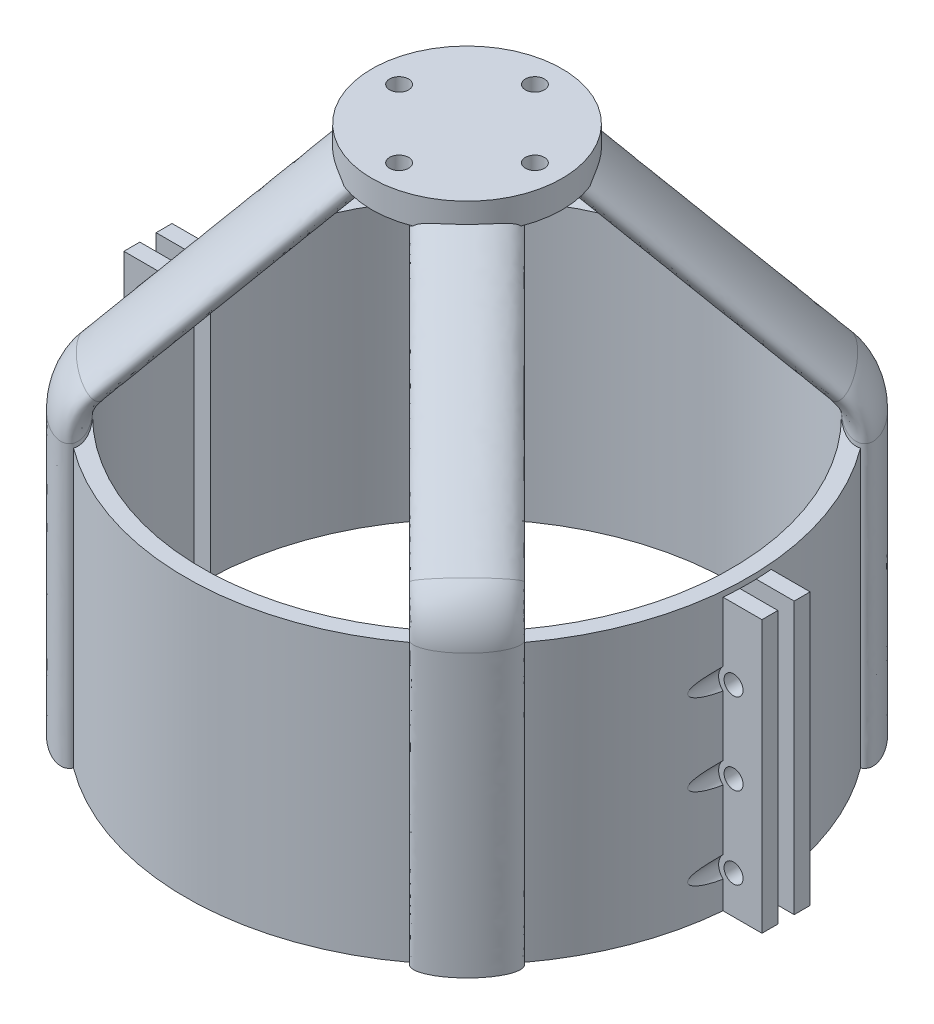
SolidWorks part; units mm, degrees
ref_plane "Front Plane" through (0, 0, 0) normal (0, 0, 1) x (1, 0, 0)
ref_plane "Top Plane" through (0, 0, 0) normal (0, 1, 0) x (1, 0, 0)
ref_plane "Right Plane" through (0, 0, 0) normal (1, 0, 0) x (0, 0, -1)
sketch "Sketch1" plane through (0, 0, 0) normal (0, 1, 0) x (1, 0, 0)
  line L0 (-68.1891, 0) -> (51.75, 0) construction
  line L1 (-58.7269, -1.5) -> (-48.7269, -1.5)
  line L2 (-58.7269, 1.5) -> (-48.7269, 1.5)
  line L3 (-58.7269, -1.5) -> (-58.7269, -4.432)
  line L4 (-58.7269, -4.432) -> (-51.5599, -4.432)
  line L5 (-58.7269, 1.5) -> (-58.7269, 4.432)
  line L6 (-58.7269, 4.432) -> (-51.5599, 4.432)
  line L7 (0, -59.7416) -> (0, 60.0429) construction
  line L8 (58.7269, -1.5) -> (48.7269, -1.5)
  line L9 (58.7269, -4.432) -> (51.5599, -4.432)
  line L10 (58.7269, -1.5) -> (58.7269, -4.432)
  line L11 (58.7269, 1.5) -> (48.7269, 1.5)
  line L12 (58.7269, 1.5) -> (58.7269, 4.432)
  line L13 (58.7269, 4.432) -> (51.5599, 4.432)
  arc A0 (-48.7269, -1.5) -> (48.7269, -1.5) centre (0, 0) ccw
  arc A1 (-51.75, 0) -> (-51.7283, -1.5) centre (0, 0) ccw
  circle A2 centre (0, 0) radius 51.75 construction
  circle A3 centre (0, 0) radius 48.75 construction
  arc A4 (-51.5599, -4.432) -> (51.5599, -4.432) centre (0, 0) ccw
  arc A5 (48.7269, 1.5) -> (-48.7269, 1.5) centre (0, 0) ccw
  arc A6 (51.5599, 4.432) -> (-51.5599, 4.432) centre (0, 0) ccw
  dimension "D1" = 97.5
  dimension "D3" = 3
  dimension "D4" = 10
  dimension "D2" = 3
extrude "Boss-Extrude1" add sketch "Sketch1" along normal blind 50 contours L4 A4 L9 L10 L8 A0 L1 L3 | A6 L6 L5 L2 A5 L11 L12 L13
sketch "Sketch2" plane through (0, 0, 4.432) normal (0, 0, 1) x (1, 0, 0)
  line L0 (0, 57.4382) -> (0, -5.5464) construction
  line L1 (-53.5, 59.7194) -> (-53.5, -8.2171) construction
  line L2 (-58.7269, 0) -> (-51.5599, 0) construction
  circle A0 centre (-53.5, 7) radius 1.75
  circle A1 centre (-53.5, 22) radius 1.75
  circle A2 centre (-53.5, 37) radius 1.75
  circle A3 centre (53.5, 7) radius 1.75
  circle A4 centre (53.5, 22) radius 1.75
  circle A5 centre (53.5, 37) radius 1.75
  dimension "D5" = 3.5
  dimension "D6" = 3.5
  dimension "D7" = 3.5
  dimension "D1" = 53.5
  dimension "D2" = 7
  dimension "D3" = 15
  dimension "D4" = 15
extrude "Cut-Extrude1" cut sketch "Sketch2" against normal through all
sketch "Sketch3" plane through (0, 0, 4.432) normal (0, 0, 1) x (1, 0, 0)
  line L0 (0, 54.5816) -> (0, -6.8451) construction
  circle A0 centre (-53.5, 37) radius 2.75
  circle A1 centre (-53.5, 22) radius 2.75
  circle A2 centre (-53.5, 7) radius 2.75
  circle A3 centre (53.5, 7) radius 2.75
  circle A4 centre (53.5, 22) radius 2.75
  circle A5 centre (53.5, 37) radius 2.75
  circle A6 centre (53.5, 7) radius 1.75 construction
  circle A7 centre (53.5, 22) radius 1.75 construction
  circle A8 centre (53.5, 37) radius 1.75 construction
  circle A9 centre (-53.5, 7) radius 1.75 construction
  circle A10 centre (-53.5, 22) radius 1.75 construction
  circle A11 centre (-53.5, 37) radius 1.75 construction
  circle A12 centre (53.5, 7) radius 1.75
  circle A13 centre (53.5, 22) radius 1.75
  circle A14 centre (53.5, 37) radius 1.75
  circle A15 centre (-53.5, 7) radius 1.75
  circle A16 centre (-53.5, 22) radius 1.75
  circle A17 centre (-53.5, 37) radius 1.75
  dimension "D2" = 5.5
  dimension "D3" = 5.5
  dimension "D4" = 5.5
extrude "Cut-Extrude3" cut sketch "Sketch3" along normal blind 50
ref_plane "Plane1" through (0, 0, 0) normal (0, 0, 1) x (0, -1, 0)
sketch "Sketch5" plane through (0, 0, -4.432) normal (0, 0, -1) x (-1, 0, 0)
  line L0 (0, 54.4273) -> (0, -7.504) construction
  line L1 (0, 50) -> (0, 0) construction
  circle A0 centre (53.5, 7) radius 1.75 construction
  circle A1 centre (53.5, 22) radius 1.75 construction
  circle A2 centre (53.5, 37) radius 1.75 construction
  circle A3 centre (-53.5, 7) radius 1.75 construction
  circle A4 centre (-53.5, 22) radius 1.75 construction
  circle A5 centre (-53.5, 37) radius 1.75 construction
  circle A6 centre (53.5, 7) radius 1.75
  circle A7 centre (53.5, 22) radius 1.75
  circle A8 centre (53.5, 37) radius 1.75
  circle A9 centre (-53.5, 7) radius 1.75
  circle A10 centre (-53.5, 22) radius 1.75
  circle A11 centre (-53.5, 37) radius 1.75
  circle A12 centre (-53.5, 37) radius 2.75
  circle A13 centre (-53.5, 22) radius 2.75
  circle A14 centre (-53.5, 7) radius 2.75
  circle A15 centre (53.5, 7) radius 2.75
  circle A16 centre (53.5, 22) radius 2.75
  circle A17 centre (53.5, 37) radius 2.75
  dimension "D1" = 5.5
  dimension "D2" = 5.5
  dimension "D3" = 5.5
extrude "Cut-Extrude4" cut sketch "Sketch5" along normal blind 50
sketch "Sketch7" plane through (0, 50, 0) normal (0, 1, 0) x (1, 0, 0)
  line L0 (0, 0) -> (-68.3441, -68.3441) construction
ref_plane "Plane2" through (0, 0, 0) normal (0.7071, 0, 0.7071) x (0.7071, 0, -0.7071)
sketch "Sketch9" plane through (0, 0, 0) normal (0.7071, 0, 0.7071) x (0.7071, 0, -0.7071)
  line L2 (0, 50) -> (0, 113.0394) construction
  line L3 (0, 50) -> (-96.6532, 50) construction
  line L4 (48.75, 50) -> (-33.3945, 50) construction
  line L5 (0, 50) -> (0, 0) construction
  line L6 (-24.7578, 95) -> (27.1814, 95) construction
  line L8 (-51.75, 0) -> (-51.75, 51.7721)
  line L16 (-51.75, 0) -> (33.3244, 0) construction
  line L17 (-48.7564, 58.9073) -> (-12, 95)
  arc A0 (-51.75, 51.7721) -> (-48.7564, 58.9073) centre (-41.75, 51.7721) cw
  dimension "D4" = 10
  dimension "D1" = 45
  dimension "D2" = 12
  dimension "D3" = 51.75
sketch "Sketch10" plane through (0, 0, 0) normal (0, -1, 0) x (1, 0, 0)
  line L0 (0, 0) -> (-68.3441, 68.3441) construction
  line L1 (-34.476, 34.476) -> (-8.4853, 8.4853) construction
  ellipse E0 centre (-36.5928, 36.5928) end of major axis (-31.2895, 41.8961) minor radius 3
  point P31 (0, 0)
  dimension "D1" = 6
  dimension "D2" = 15
sweep "Sweep1" add profiles "Sketch10" path "Sketch9"
sketch "Sketch11" plane through (0, 50, 0) normal (0, 1, 0) x (1, 0, 0)
  circle A0 centre (0, 0) radius 48.75
  circle A1 centre (0, 0) radius 51.75
extrude "Boss-Extrude2" add sketch "Sketch11" along normal blind 1
pattern_circular "CirPattern3" count 4 over 360 about axis through (0, 50, 0) along (0, 1, 0) of "Sweep1"
ref_plane "Plane3" through (0, 95, 0) normal (0, 1, 0) x (1, 0, 0)
sketch "Sketch12" plane through (0, 95, 0) normal (0, 1, 0) x (1, 0, 0)
  circle A0 centre (0, 0) radius 17.5
  dimension "D1" = 35
extrude "Boss-Extrude3" add sketch "Sketch12" along normal blind 2.5 and the other way blind 2.5
sketch "Sketch13" plane through (0, 97.5, 0) normal (0, 1, 0) x (1, 0, 0)
  line L0 (0, 0) -> (0, 30.3025) construction
  circle A0 centre (0, 12.5) radius 1.75
  circle A1 centre (12.5, 0) radius 1.75
  circle A2 centre (0, -12.5) radius 1.75
  circle A3 centre (-12.5, 0) radius 1.75
  point P14 (0, 0)
  dimension "D1" = 3.5
  dimension "D2" = 12.5
  dimension "D3" = 4
extrude "Cut-Extrude5" cut sketch "Sketch13" against normal blind 5
